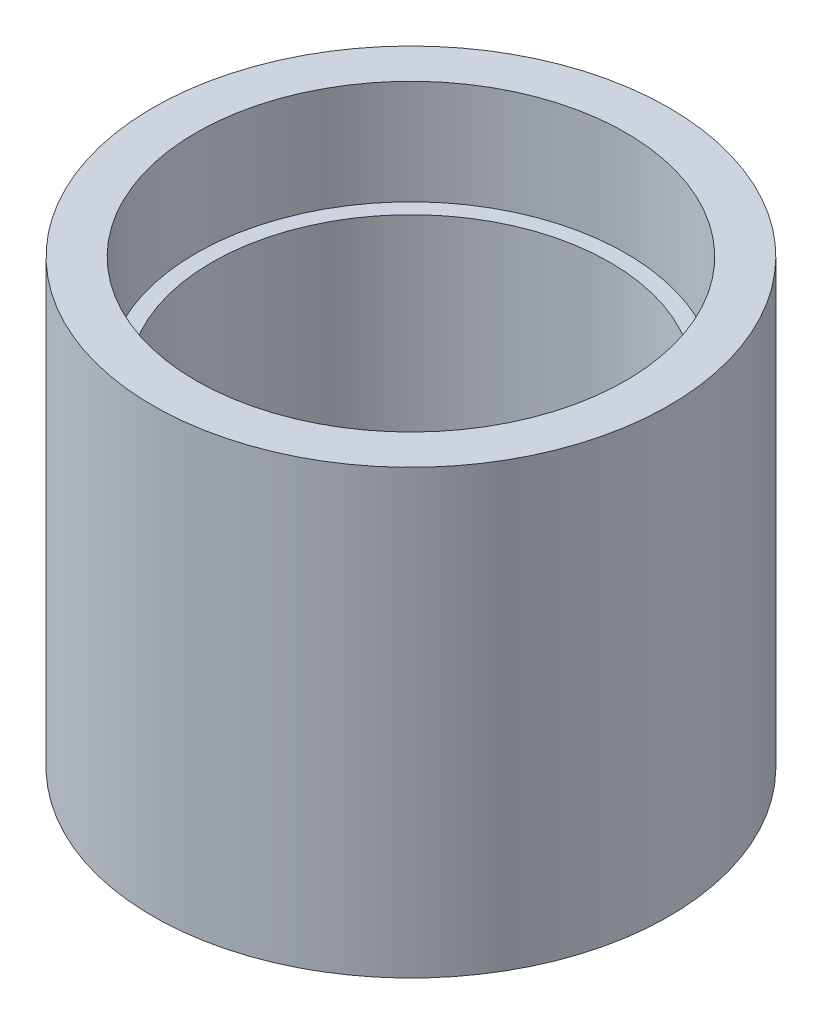
SolidWorks part; units mm, degrees
ref_plane "Front Plane" through (0, 0, 0) normal (0, 0, 1) x (1, 0, 0)
ref_plane "Top Plane" through (0, 0, 0) normal (0, 1, 0) x (1, 0, 0)
ref_plane "Right Plane" through (0, 0, 0) normal (1, 0, 0) x (0, 0, -1)
sketch "Sketch1" plane through (0, 0, 0) normal (0, 1, 0) x (1, 0, 0)
  circle A0 centre (0, 0) radius 22.225
  dimension "D1" = 44.45
extrude "Boss-Extrude1" add sketch "Sketch1" along normal blind 38.1
sketch "Sketch2" plane through (0, 38.1, 0) normal (0, 1, 0) x (1, 0, 0)
  circle A0 centre (0, 0) radius 18.5039
  dimension "D1" = 37.0078
extrude "Cut-Extrude1" cut sketch "Sketch2" against normal blind 8.9916
sketch "Sketch4" plane through (0, 0, 0) normal (0, -1, 0) x (1, 0, 0)
  circle A0 centre (0, 0) radius 18.5039
  dimension "D1" = 37.0078
extrude "Cut-Extrude2" cut sketch "Sketch4" against normal blind 8.9916
sketch "Sketch5" plane through (0, 8.9916, 0) normal (0, -1, 0) x (1, 0, 0)
  circle A0 centre (0, 0) radius 17.145
  dimension "D1" = 34.29
extrude "Cut-Extrude3" cut sketch "Sketch5" against normal through all
